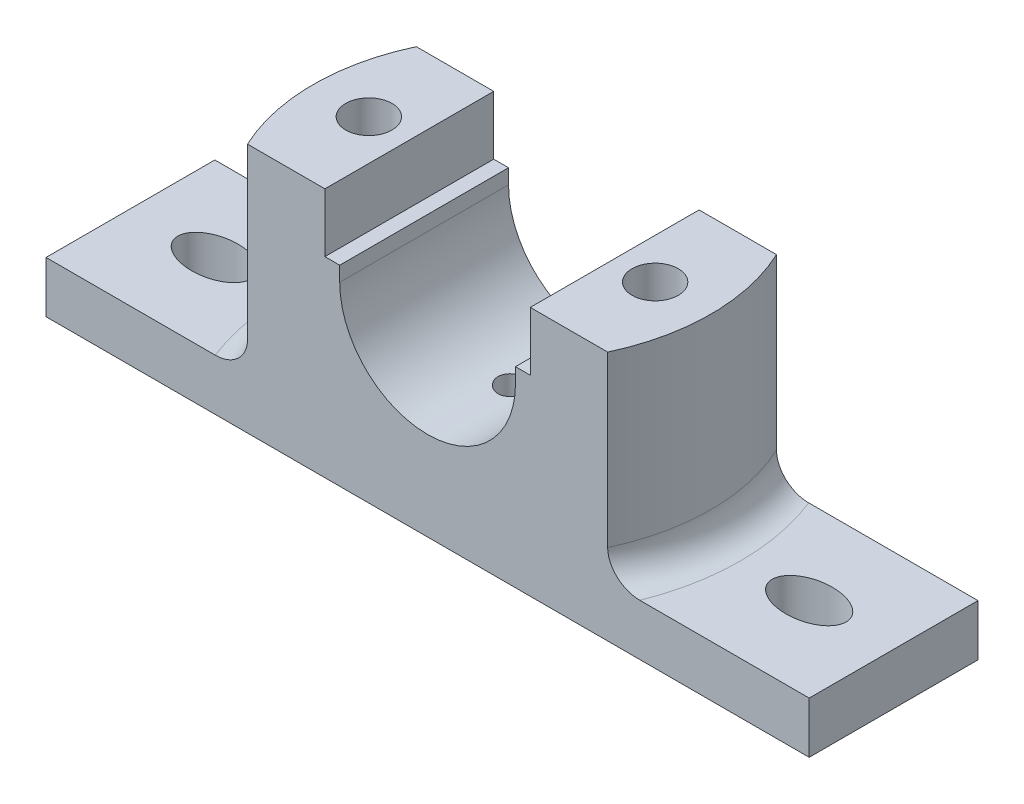
SolidWorks part; units mm, degrees
ref_plane "Front Plane" through (0, 0, 0) normal (0, 0, 1) x (1, 0, 0)
ref_plane "Top Plane" through (0, 0, 0) normal (0, 1, 0) x (1, 0, 0)
ref_plane "Right Plane" through (0, 0, 0) normal (1, 0, 0) x (0, 0, -1)
sketch "Sketch2" plane through (0, 0, 0) normal (0, 0, 1) x (1, 0, 0)
  line L0 (0, 0) -> (0, 11.1)
  line L1 (0, 11.1) -> (39.5, 11.1)
  line L2 (39.5, 11.1) -> (39.5, 54.1)
  line L3 (39.5, 54.1) -> (60.3, 54.1)
  line L4 (60.3, 54.1) -> (60.3, 41.4)
  line L5 (60.3, 41.4) -> (63.5, 41.4)
  line L6 (63.5, 41.4) -> (63.5, 38.2)
  line L8 (82.5, 19.2) -> (82.5, 0)
  line L9 (82.5, 0) -> (0, 0)
  arc A1 (63.5, 38.2) -> (82.5, 19.2) centre (82.5, 38.2) ccw
  point P12 (82.5, 38.2)
  dimension "D9" = 38
  dimension "D1" = 11.1
  dimension "D2" = 82.5
  dimension "D3" = 3.2
  dimension "D4" = 12.7
  dimension "D5" = 22.2
  dimension "D6" = 43
  dimension "D7" = 43
extrude "Boss-Extrude1" add sketch "Sketch2" along normal mid plane 36.5 contours L5 L6 A1 L8 L9 L0 L1 L2 L3 L4
sketch "Sketch3" plane through (0, 54.1, 0) normal (0, 1, 0) x (1, 0, 0)
  line L0 (82.5, -18.25) -> (82.5, 18.25) construction
  line L4 (39.5, -18.25) -> (60.3, -18.25) construction
  line L5 (39.5, -18.25) -> (39.5, 18.25) construction
  line L10 (39.5, -18.25) -> (43.565, -18.25)
  line L11 (39.5, -18.25) -> (39.5, 0)
  arc A1 (39.5, 0) -> (43.565, -18.25) centre (82.5, 0) ccw
  dimension "D1" = 86
extrude "Cut-Extrude1" cut sketch "Sketch3" against normal blind 43 and the other way blind 5
mirror "Mirror2" about plane through (0, 0, 0) normal (0, 0, 1) of "Cut-Extrude1"
mirror "Mirror3" about plane through (82.5, 19.2, 18.25) normal (1, 0, 0) of bodies 104
sketch "Sketch6" plane through (0, 54.1, 0) normal (0, 1, 0) x (1, 0, 0)
  line L0 (82.5, -18.25) -> (82.5, 18.25) construction
  circle A0 centre (51.55, 0) radius 5
  dimension "D2" = 10
  dimension "D1" = 30.95
sketch "Sketch7" plane through (0, 11.1, 0) normal (0, 1, 0) x (1, 0, 0)
  line L0 (82.5, -18.25) -> (82.5, 18.25) construction
  ellipse E0 centre (18.25, 0) end of major axis (26.25, 0) minor radius 5
  dimension "D1" = 64.25
extrude "Cut-Extrude3" cut sketch "Sketch6" against normal up to surface (54.1 mm away) contours A0 up to face at (82.5, 0, 0)
extrude "Cut-Extrude4" cut sketch "Sketch7" against normal up to surface (11.1 mm away) contours E0 up to face at (56.55, 0, 0)
ref_plane "Plane1" through (82.5, 0, 0) normal (-1, 0, 0) x (0, 0, 1)
mirror "Mirror4" about plane through (82.5, 0, 0) normal (-1, 0, 0) of "Cut-Extrude4", "Cut-Extrude3"
fillet "Fillet3" radius 6.4 2 edges at (125.5, 11.1, 0) (39.5, 11.1, 0)
sketch "Sketch10" plane through (0, 0, 0) normal (0, -1, 0) x (1, 0, 0)
  line L0 (0, 18.25) -> (0, -18.25) construction
  line L1 (7, 11.25) -> (158, 11.25)
  line L2 (7, 11.25) -> (7, -11.25)
  line L3 (7, -11.25) -> (158, -11.25)
  line L4 (158, 11.25) -> (158, -11.25)
  line L5 (165, 18.25) -> (0, 18.25) construction
  line L6 (165, -18.25) -> (0, -18.25) construction
  line L7 (165, 18.25) -> (165, -18.25) construction
  dimension "D1" = 7
  dimension "D2" = 7
  dimension "D3" = 7
  dimension "D4" = 7
extrude "Cut-Extrude7" cut sketch "Sketch10" against normal blind 2.5
sketch "Sketch11" plane through (0, 0, 0) normal (0, -1, 0) x (1, 0, 0)
  line L1 (41.05, 10.5) -> (62.05, 10.5)
  line L2 (41.05, 10.5) -> (41.05, -10.5)
  line L3 (41.05, -10.5) -> (62.05, -10.5)
  line L4 (62.05, 10.5) -> (62.05, -10.5)
  line L5 (41.05, 10.5) -> (62.05, -10.5) construction
  line L6 (41.05, -10.5) -> (62.05, 10.5) construction
  point P0 (51.55, 0)
  dimension "D1" = 21
  dimension "D2" = 21
extrude "Cut-Extrude8" cut sketch "Sketch11" against normal blind 8
mirror "Mirror5" about plane through (82.5, 0, 0) normal (-1, 0, 0) of "Cut-Extrude8"
sketch "Sketch12" plane through (82.5, 0, 0) normal (-1, 0, 0) x (0, 0, 1)
  line L0 (0, 19.5) -> (3, 19.5)
  line L1 (0, 8) -> (0, 54.1) construction
  line L2 (0, 8) -> (0, 54.1) construction
  line L3 (3, 19.5) -> (3, 13.5)
  line L4 (3, 13.5) -> (0, 9.9837)
  line L5 (0, 9.9837) -> (0, 19.5)
  line L9 (18.25, 0) -> (-18.25, 0) construction
  dimension "D1" = 3
  dimension "D2" = 6
  dimension "D3" = 19.5
revolve "Cut-Revolve1" cut sketch "Sketch12" angle 360 about axis through (82.5, 59.1, 0) along (0, -1, 0)
equation "\"mm\"=36.5"
